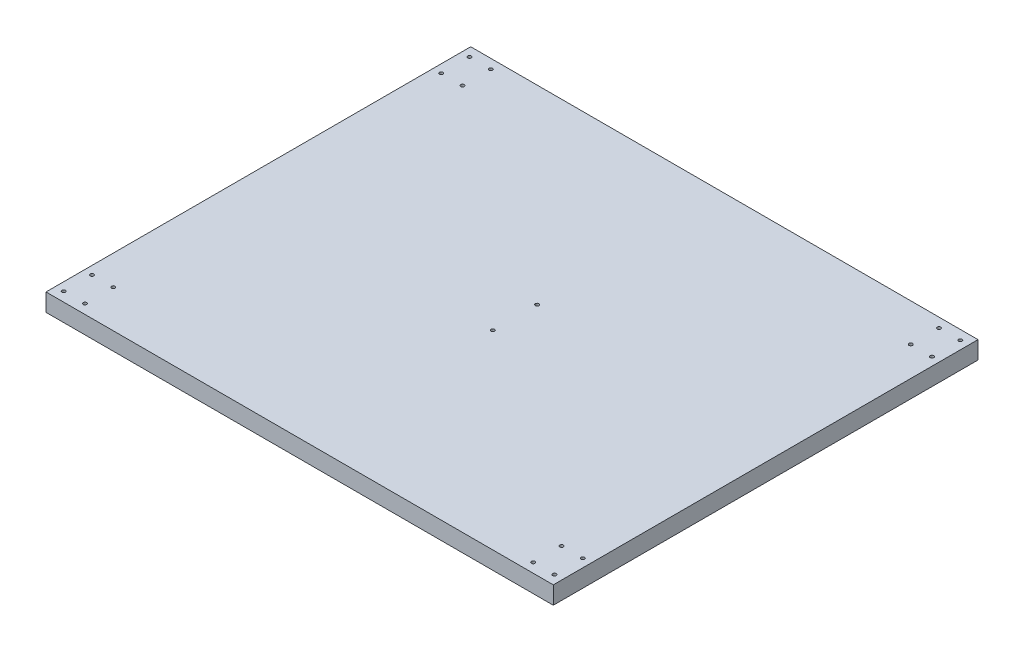
SolidWorks part; units mm, degrees
ref_plane "Alzado" through (0, 0, 0) normal (0, 0, 1) x (1, 0, 0)
ref_plane "Planta" through (0, 0, 0) normal (0, 1, 0) x (1, 0, 0)
ref_plane "Vista lateral" through (0, 0, 0) normal (1, 0, 0) x (0, 0, -1)
sketch "Croquis1" plane through (0, 0, 0) normal (0, 1, 0) x (1, 0, 0)
  line L0 (0, -180) -> (0, 180) construction
  line L1 (-215, -180) -> (215, -180)
  line L2 (-215, -180) -> (-215, 180)
  line L3 (-215, 180) -> (215, 180)
  line L4 (215, -180) -> (215, 180)
  line L5 (-215, -180) -> (215, 180) construction
  line L6 (-215, 180) -> (215, -180) construction
  circle A2 centre (2.5, 18.8) radius 1.5
  circle A3 centre (2.5, -18.8) radius 1.5
  point P0 (0, 0)
  dimension "D6" = 3
  dimension "D1" = 430
  dimension "D2" = 360
  dimension "D7" = 2.5
  dimension "D8" = 18.8
  dimension "D9" = 18.8
extrude "Saliente-Extruir1" add sketch "Croquis1" along normal blind 15
sketch "Croquis2" plane through (0, 15, 0) normal (0, 1, 0) x (1, 0, 0)
  line L0 (0, 180) -> (0, -180) construction
  line L1 (215, 180) -> (-215, 180) construction
  line L2 (-215, -180) -> (215, -180) construction
  line L3 (-177, 180) -> (-177, -180) construction
  line L4 (177, 180) -> (177, -180) construction
  line L5 (-215, 0) -> (215, 0) construction
  line L6 (-215, 180) -> (-215, -180) construction
  line L7 (215, -180) -> (215, 180) construction
  line L8 (-177, 167) -> (177, 167) construction
  line L9 (-177, -167) -> (177, -167) construction
  dimension "D1" = 177
  dimension "D2" = 177
  dimension "D3" = 167
  dimension "D4" = 167
sketch "Croquis3" plane through (0, 15, 0) normal (0, 1, 0) x (1, 0, 0)
  line L2 (0, 180) -> (0, -180) construction
  line L3 (-215, 0) -> (215, 0) construction
  circle A0 centre (208, -172) radius 1.5
  circle A1 centre (190, -172) radius 1.5
  circle A2 centre (190, -148) radius 1.5
  circle A3 centre (208, -148) radius 1.5
  circle A4 centre (-208, -172) radius 1.5
  circle A5 centre (-190, -172) radius 1.5
  circle A6 centre (-208, -148) radius 1.5
  circle A7 centre (-190, -148) radius 1.5
  circle A8 centre (-208, 172) radius 1.5
  circle A9 centre (-190, 172) radius 1.5
  circle A10 centre (-190, 148) radius 1.5
  circle A11 centre (-208, 148) radius 1.5
  circle A12 centre (208, 172) radius 1.5
  circle A13 centre (190, 172) radius 1.5
  circle A14 centre (190, 148) radius 1.5
  circle A15 centre (208, 148) radius 1.5
  dimension "D1" = 3
  dimension "D2" = 24
  dimension "D4" = 148
  dimension "D5" = 18
  dimension "D6" = 190
extrude "Cortar-Extruir1" cut sketch "Croquis3" against normal through all
